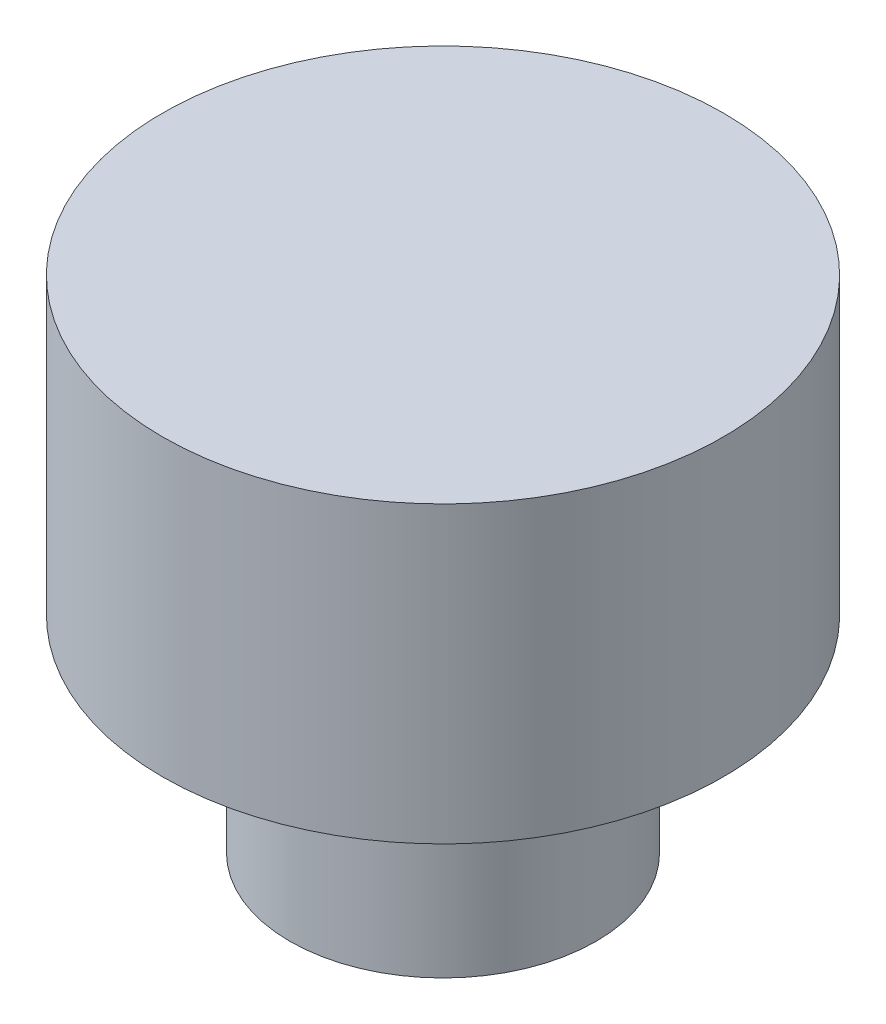
SolidWorks part; units mm, degrees
ref_plane "Front Plane" through (0, 0, 0) normal (0, 0, 1) x (1, 0, 0)
ref_plane "Top Plane" through (0, 0, 0) normal (0, 1, 0) x (1, 0, 0)
ref_plane "Right Plane" through (0, 0, 0) normal (1, 0, 0) x (0, 0, -1)
sketch "Sketch1" plane through (0, 0, 0) normal (0, 1, 0) x (1, 0, 0)
  circle A0 centre (0, 0) radius 3.2
  circle A1 centre (0, 0) radius 5.2
  dimension "D1" = 6.4
  dimension "D2" = 2
extrude "Boss-Extrude1" add sketch "Sketch1" along normal blind 7
sketch "Sketch2" plane through (0, 7, 0) normal (0, 1, 0) x (1, 0, 0)
  circle A0 centre (0, 0) radius 9.525
  dimension "D1" = 19.05
extrude "Boss-Extrude2" add sketch "Sketch2" along normal blind 10
sketch "Sketch3" plane through (0, 7, 0) normal (0, -1, 0) x (1, 0, 0)
  line L1 (-3.2, 0.7) -> (3.2, 0.7)
  line L2 (-3.2, 0.7) -> (-3.2, -0.7)
  line L3 (-3.2, -0.7) -> (3.2, -0.7)
  line L4 (3.2, 0.7) -> (3.2, -0.7)
  line L5 (-3.2, 0.7) -> (3.2, -0.7) construction
  line L6 (-3.2, -0.7) -> (3.2, 0.7) construction
  circle A1 centre (0, 0) radius 3.2
  circle A2 centre (0, 0) radius 3.2
  point P0 (0, 0)
  circle M5 centre (0, 0) radius 3.2
  dimension "D2" = 1.4
  dimension "D1" = 0
extrude "Boss-Extrude3" add sketch "Sketch3" along normal blind 0.8 contours L3 L1 M5
